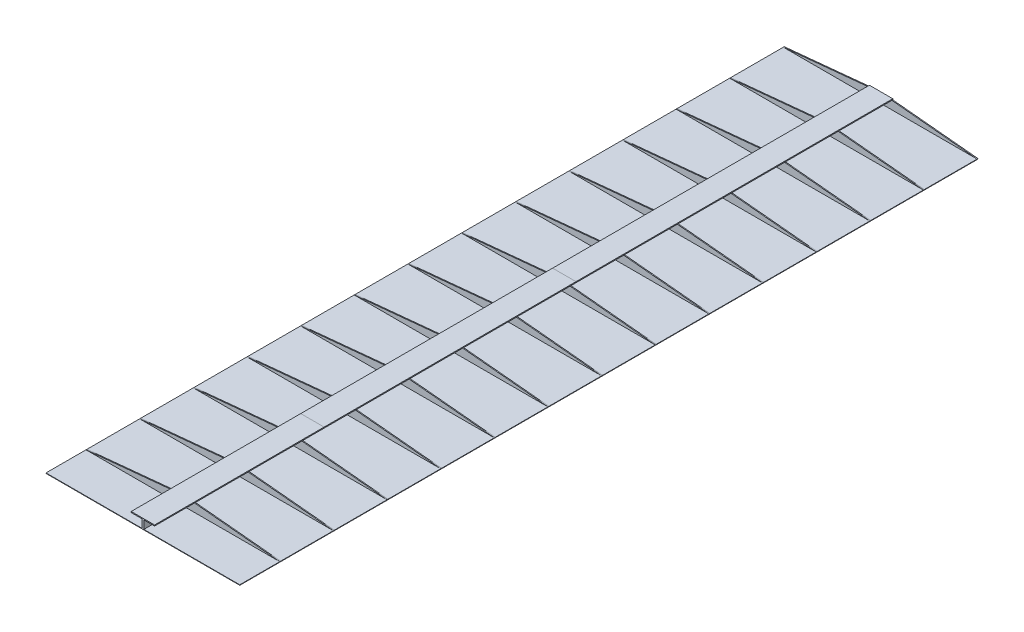
SolidWorks part; units mm, degrees
material "6061-T6 (SS)"
ref_plane "Front Plane" through (0, 0, 0) normal (0, 0, 1) x (1, 0, 0)
ref_plane "Top Plane" through (0, 0, 0) normal (0, 1, 0) x (1, 0, 0)
ref_plane "Right Plane" through (0, 0, 0) normal (1, 0, 0) x (0, 0, -1)
sketch "Sketch1" plane through (0, 0, 0) normal (0, 0, 1) x (1, 0, 0)
  line L0 (-90, 95) -> (151.3, 95)
  line L1 (151.3, 95) -> (151.3, 0)
  line L2 (151.3, 0) -> (1030.65, 0)
  line L3 (1030.65, 0) -> (1030.65, -5)
  line L4 (1030.65, -5) -> (-969.35, -5)
  line L5 (-969.35, -5) -> (-969.35, 0)
  line L6 (-969.35, 0) -> (-90, 0)
  line L7 (-90, 0) -> (-90, 95)
  dimension "D1" = 100
  dimension "D2" = 241.3
  dimension "D3" = 90
  dimension "D4" = 5
  dimension "D5" = 2000
extrude "Boss-Extrude1" add sketch "Sketch1" against normal blind 7620
sketch "Sketch7" plane through (0, 0, -7620) normal (0, 0, -1) x (-1, 0, 0)
  line L0 (-151.3, 0) -> (-151.3, 95) construction
  line L1 (-151.3, 85) -> (-40.65, 85)
  line L2 (-151.3, 85) -> (-151.3, 0)
  line L3 (-151.3, 0) -> (-40.65, 0)
  line L4 (-40.65, 85) -> (-40.65, 0)
  line L5 (-151.3, 95) -> (90, 95) construction
  line L6 (969.35, -5) -> (-1030.65, -5) construction
  line L7 (90, 95) -> (90, 0) construction
  line L8 (90, 85) -> (-20.65, 85)
  line L9 (90, 85) -> (90, 0)
  line L10 (90, 0) -> (-20.65, 0)
  line L11 (-20.65, 85) -> (-20.65, 0)
  dimension "D1" = 10
  dimension "D2" = 5
  dimension "D3" = 20
extrude "Cut-Extrude3" cut sketch "Sketch7" against normal through all
ref_plane "Plane1" through (30.65, 0, 0) normal (1, 0, 0) x (0, 0, -1)
sketch "Sketch8" plane through (0, 0, -7620) normal (0, 0, -1) x (-1, 0, 0)
  line L0 (-40.65, 0) -> (-40.65, 85)
  line L1 (-40.65, 85) -> (-151.3, 85)
  line L2 (-151.3, 85) -> (-1030.65, 0)
  line L3 (-1030.65, 0) -> (-40.65, 0)
extrude "Boss-Extrude3" add sketch "Sketch8" against normal blind 9.525
pattern_linear "LPattern2" count 14 spacing 553.68 along (0, 0, 1) of "Boss-Extrude3"
mirror "Mirror2" about plane through (30.65, 0, 0) normal (1, 0, 0) of "LPattern2", "Boss-Extrude3"
sketch "Sketch9" plane through (0, 95, 0) normal (0, 1, 0) x (1, 0, 0)
  line L0 (151.3, 7620) -> (151.3, 0) construction
  line L1 (151.3, 1750) -> (-90, 1750)
  line L2 (151.3, 1750) -> (151.3, 4350)
  line L3 (151.3, 4350) -> (-90, 4350)
  line L4 (-90, 1750) -> (-90, 4350)
  line L5 (-90, 7620) -> (-90, 0) construction
  line L6 (151.3, 0) -> (-90, 0) construction
  dimension "D1" = 2600
  dimension "D2" = 1750
split line "Split Line2"
